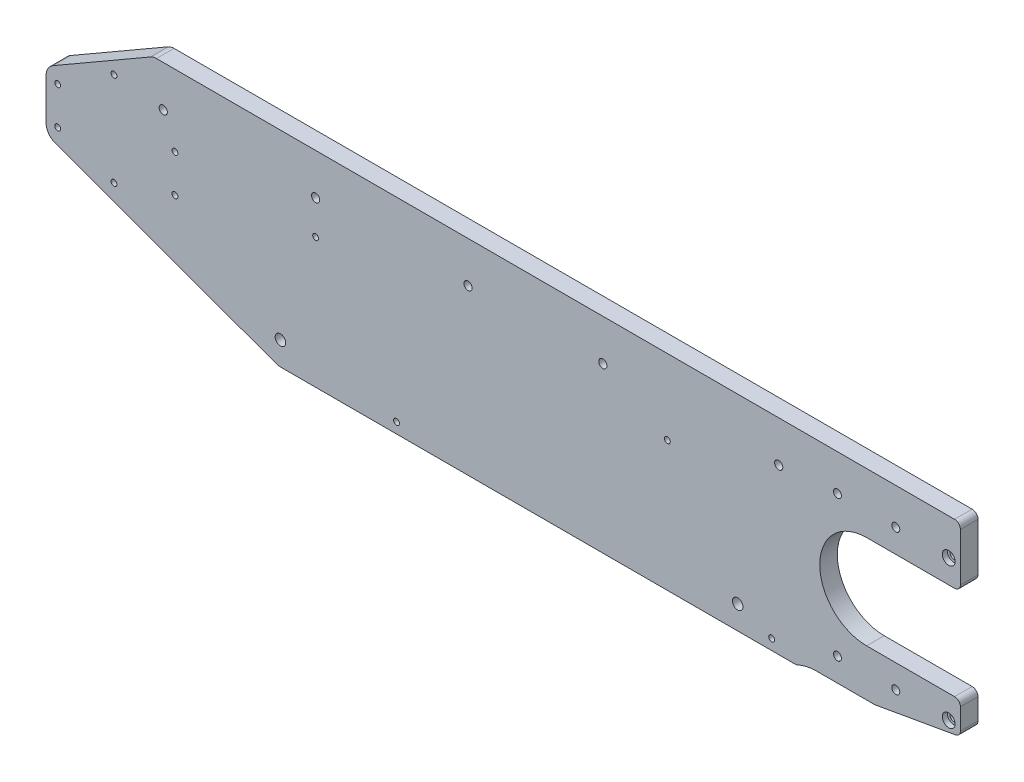
SolidWorks part; units mm, degrees
material "3.3535 (AlMg3) eloxiert"
ref_plane "Vorne" through (0, 0, 0) normal (0, 0, 1) x (1, 0, 0)
ref_plane "Oben" through (0, 0, 0) normal (0, 1, 0) x (1, 0, 0)
ref_plane "Rechts" through (0, 0, 0) normal (1, 0, 0) x (0, 0, -1)
sketch "Skizze1" plane through (0, 0, 0) normal (0, 0, 1) x (1, 0, 0)
  line L0 (127.9423, 0) -> (-256.3507, 0) construction
  line L1 (0, 40) -> (75, 40)
  line L2 (0, -40) -> (75, -40)
  line L3 (75.8682, -67.8565) -> (7.4299, -79.924)
  line L4 (80, 45) -> (80, 86)
  line L5 (-700, -3.4452) -> (-700, 31.2241)
  line L6 (80, -45) -> (80, -62.9325)
  line L7 (-610.7856, 89.6603) -> (-694, 41.6164)
  line L8 (0, -40) -> (0, -80) construction
  line L10 (-42.5644, -80) -> (6.5616, -80)
  line L11 (-605.7856, 91) -> (75, 91)
  line L12 (-692.1042, -14.7216) -> (-503.4202, -83.3969)
  line L14 (-61.1116, -84) -> (-500, -84)
  line L31 (-590, -2) -> (-690, -2) construction
  line L32 (-590, -2) -> (-590, 30) construction
  line L33 (-590, 30) -> (-690, 30) construction
  line L34 (-690, -2) -> (-690, 30) construction
  arc A0 (0, 40) -> (0, -40) centre (0, 0) ccw
  circle A1 centre (0, 0) radius 65 construction
  arc A2 (80, -62.9325) -> (75.8682, -67.8565) centre (75, -62.9325) cw
  arc A3 (75, -40) -> (80, -45) centre (75, -45) cw
  arc A4 (80, 86) -> (75, 91) centre (75, 86) ccw
  arc A5 (6.5616, -80) -> (7.4299, -79.924) centre (6.5616, -75) ccw
  arc A6 (-42.5644, -80) -> (-59.0508, -83.5556) centre (-42.5644, -120) ccw
  arc A7 (-59.0508, -83.5556) -> (-61.1116, -84) centre (-61.1116, -79) cw
  arc A8 (75, 40) -> (80, 45) centre (75, 45) ccw
  circle A9 centre (0, 0) radius 80 construction
  arc A10 (-610.7856, 89.6603) -> (-605.7856, 91) centre (-605.7856, 81) cw
  arc A11 (-503.4202, -83.3969) -> (-500, -84) centre (-500, -74) ccw
  circle A20 centre (-690, 30) radius 2.5
  circle A21 centre (-590, -2) radius 2.5
  arc A24 (-694, 41.6164) -> (-700, 31.2241) centre (-688, 31.2241) ccw
  arc A29 (-692.1042, -14.7216) -> (-700, -3.4452) centre (-688, -3.4452) cw
  point P26 (-60, -84)
  point P43 (-501.7633, -84)
  point P86 (-700, 38.1523)
  point P89 (-700, -11.8477)
  dimension "D3" = 80
  dimension "D5" = 200
  dimension "D7" = 80
  dimension "D8" = 91
  dimension "D9" = 175
  dimension "D13" = 130
  dimension "D15" = 5
  dimension "D11" = 5
  dimension "D6" = 10
  dimension "D16" = 60
  dimension "D17" = 5
  dimension "D22" = 30
  dimension "D23" = 20
  dimension "D39" = 5
  dimension "D10" = 780
  dimension "D45" = 100
  dimension "D47" = 50
  dimension "D14" = 160
  dimension "D25" = 5
  dimension "D42" = 10
  dimension "D48" = 12
  dimension "D29" = 10
  dimension "D12" = 40
  dimension "D28" = 82
  dimension "D43" = 32
extrude "Aufsatz-Linear austragen1" add sketch "Skizze1" along normal mid plane 15
hole_wizard "M6 Gewindebohrung1" positions "Skizze3" profile "Skizze2" tap size "M6" standard "Gabler-Normteile" end condition through all
sketch "Skizze3" plane through (0, 0, 7.5) normal (0, 0, 1) x (1, 0, 0)
  line L50 (140.2593, 0) -> (-309.5133, 0) construction
  line L60 (-590, -2) -> (-590, 30) construction
  line L61 (-690, 30) -> (-690, -2) construction
  line L62 (-500, -84) -> (-61.1116, -84) construction
  line L63 (-700, 31.2241) -> (-700, -3.4452) construction
  line L65 (75, 91) -> (-605.7856, 91) construction
  point P332 (-590, 30)
  point P334 (-690, -2)
  point P347 (-642, 61)
  point P350 (-642, -19)
  dimension "D5" = 80
  dimension "D6" = 58
  dimension "D4" = 65
  dimension "D7" = 84
  dimension "D8" = 91
sketch "Skizze2" plane through (-590, 30, 7.5) normal (1, 0, 0) x (0, -1, 0)
  line L0 (0, 0) -> (0, 15)
  line L1 (0, 15) -> (2.5, 15)
  line L2 (2.5, 15) -> (2.5, 0)
  line L5 (2.5, 0) -> (0, 0)
  line L11 (0, -6.35) -> (0, 107.95) construction
  dimension "Bohrerdurchmesser" = 5
  dimension "Bohrungstiefe" = 15
cosmetic thread "Bohrungsgewinde21" parameters "D2"=6
cosmetic thread "Bohrungsgewinde22" parameters "D2"=6
cosmetic thread "Bohrungsgewinde23" parameters "D2"=6
cosmetic thread "Bohrungsgewinde24" parameters "D2"=6
hole_wizard "M8 Gewindebohrung1" positions "Skizze7" profile "Skizze6" tap size "M8" standard "Gabler-Normteile" end condition through all
sketch "Skizze7" plane through (0, 0, 7.5) normal (0, 0, 1) x (1, 0, 0)
  line L15 (0, 0) -> (0, 249.0644) construction
  line L17 (0, 0) -> (-24.8744, -60.0522) construction
  line L19 (0, 0) -> (151.5757, 0) construction
  circle A0 centre (0, 0) radius 65 construction
  point P1 (-24.8744, -60.0522)
  point P35 (-24.8744, 60.0522)
  point P37 (24.8744, 60.0522)
  point P38 (24.8744, -60.0522)
  dimension "D1" = 130
  dimension "D2" = 22.5
sketch "Skizze6" plane through (-24.8744, -60.0522, 7.5) normal (1, 0, 0) x (0, -1, 0)
  line L0 (0, 0) -> (0, 15)
  line L1 (0, 15) -> (3.4, 15)
  line L2 (3.4, 15) -> (3.4, 0)
  line L5 (3.4, 0) -> (0, 0)
  line L11 (0, -6.35) -> (0, 107.95) construction
  dimension "Bohrerdurchmesser" = 6.8
  dimension "Bohrungstiefe" = 15
cosmetic thread "Bohrungsgewinde5" parameters "D2"=8
cosmetic thread "Bohrungsgewinde8" parameters "D2"=8
cosmetic thread "Bohrungsgewinde19" parameters "D2"=8
cosmetic thread "Bohrungsgewinde20" parameters "D2"=8
hole_wizard "Durchgangsloch für M81" positions "Skizze5" profile "Skizze4" hole size "M8" standard "Gabler-Normteile" end condition through all
sketch "Skizze5" plane through (0, 0, 7.5) normal (0, 0, 1) x (1, 0, 0)
  line L14 (-500, -84) -> (-61.1116, -84) construction
  line L17 (80, 45) -> (80, 86) construction
  point P41 (-500, -64)
  point P70 (-110, -64)
  dimension "D1" = 390
  dimension "D3" = 20
  dimension "D6" = 190
sketch "Skizze4" plane through (-500, -64, 7.5) normal (1, 0, 0) x (0, -1, 0)
  line L0 (0, 0) -> (0, 15)
  line L1 (0, 15) -> (4.5, 15)
  line L2 (4.5, 15) -> (4.5, 0)
  line L5 (4.5, 0) -> (0, 0)
  line L11 (0, -6.35) -> (0, 107.95) construction
  dimension "Bohrerdurchmesser" = 9
  dimension "Bohrungstiefe" = 15
hole_wizard "Ø5.0 (5) Durchmesser Bohrung1" positions "Skizze9" profile "Skizze8" hole size "Ø5.0" standard "DIN" end condition through all
sketch "Skizze9" plane through (0, 0, 7.5) normal (0, 0, 1) x (1, 0, 0)
  line L0 (-470, 27) -> (-170, 27) construction
  line L4 (80, 45) -> (80, 86) construction
  line L5 (-500, -84) -> (-61.1116, -84) construction
  point P17 (-170, 27)
  point P26 (-470, 27)
other "AusrichtungGruppe1" parameters "D1"=792.0272, "D2"=114.3676, "D3"=200, "D4"=200, "D5"=200, "D6"=200, "D7"=678.5, "D8"=897.5, "D9"=1117.5, "D10"=1337.5, "D11"=1557.5, "D12"=1760, "D13"=1860, "D14"=1960, "D15"=100
sketch "Skizze8" plane through (-170, 27, 7.5) normal (1, 0, 0) x (0, -1, 0)
  line L0 (0, 0) -> (0, 15)
  line L1 (0, 15) -> (2.5, 15)
  line L2 (2.5, 15) -> (2.5, 0)
  line L5 (2.5, 0) -> (0, 0)
  line L11 (0, -6.35) -> (0, 107.95) construction
  dimension "Bohrerdurchmesser" = 5
  dimension "Bohrungstiefe" = 15
hole_wizard "Stirnsenkung für M6 Zylinderschraube mit Innensechskant1" positions "Skizze22" profile "Skizze21" counterbore size "M6" standard "Gabler-Normteile" end condition through all
sketch "Skizze22" plane through (0, 0, 7.5) normal (0, 0, 1) x (1, 0, 0)
  line L3 (-40, 0) -> (0, 0) construction
  arc A1 (0, 40) -> (0, -40) centre (0, 0) ccw construction
  point P14 (70, 60)
  point P16 (70, -60)
  dimension "D4" = 120
  dimension "D5" = 70
sketch "Skizze21" plane through (70, 60, 7.5) normal (1, 0, 0) x (0, -1, 0)
  line L0 (0, 0) -> (0, 15)
  line L1 (0, 15) -> (3.3, 15)
  line L3 (3.3, 15) -> (3.3, 4.4)
  line L4 (3.3, 4.4) -> (5.5, 4.4)
  line L5 (5.5, 4.4) -> (5.5, 0)
  line L7 (5.5, 0) -> (0, 0)
  line L11 (0, -6.35) -> (0, 107.95) construction
  dimension "Bohrerdurchmesser" = 6.6
  dimension "Bohrungstiefe" = 15
  dimension "Senkdurchmesser2" = 11
  dimension "Senktiefe2" = 4.4
mirror "Spiegeln1" about plane through (0, 0, 0) normal (0, 0, 1) of "Stirnsenkung für M6 Zylinderschraube mit Innensechskant1"
hole_wizard "Ø7.0 (7) Durchmesser Bohrung2" positions "Skizze32" profile "Skizze31" hole size "Ø7.0" standard "Gabler-Normteile" end condition through all
sketch "Skizze32" plane through (0, 0, 7.5) normal (0, 0, 1) x (1, 0, 0)
  line L0 (80, 45) -> (80, 86) construction
  circle A1 centre (70, 60) radius 3.3 construction
  point P0 (-75, 56)
  point P12 (-225, 56)
  point P14 (-340, 56)
  point P16 (-470, 56)
  point P18 (-600, 56)
other "AusrichtungGruppe3" parameters "D1"=6.6, "D2"=0, "D3"=155, "D4"=305, "D5"=420, "D6"=550, "D7"=680, "D8"=900
sketch "Skizze31" plane through (-75, 56, 7.5) normal (1, 0, 0) x (0, -1, 0)
  line L0 (0, 0) -> (0, 15)
  line L1 (0, 15) -> (3.5, 15)
  line L2 (3.5, 15) -> (3.5, 0)
  line L5 (3.5, 0) -> (0, 0)
  line L11 (0, -6.35) -> (0, 107.95) construction
  dimension "Bohrerdurchmesser" = 7
  dimension "Bohrungstiefe" = 15
hole_wizard "M6 Gewindebohrung2" positions "Skizze34" profile "Skizze33" tap size "M6" standard "Gabler-Normteile" end condition through all
sketch "Skizze34" plane through (0, 0, -7.5) normal (0, 0, -1) x (-1, 0, 0)
  line L0 (500, -84) -> (61.1116, -84) construction
  line L1 (700, 31.2241) -> (700, -3.4452) construction
  point P0 (81, -75)
  point P2 (401, -75)
  dimension "D1" = 9
  dimension "D2" = 619
  dimension "D3" = 320
sketch "Skizze33" plane through (-81, -75, -7.5) normal (1, 0, 0) x (0, 1, 0)
  line L0 (0, 0) -> (0, 15)
  line L1 (0, 15) -> (2.5, 15)
  line L2 (2.5, 15) -> (2.5, 0)
  line L5 (2.5, 0) -> (0, 0)
  line L11 (0, -6.35) -> (0, 107.95) construction
  dimension "Bohrerdurchmesser" = 5
  dimension "Bohrungstiefe" = 15
cosmetic thread "Bohrungsgewinde25" parameters "D2"=6
cosmetic thread "Bohrungsgewinde26" parameters "D2"=6
